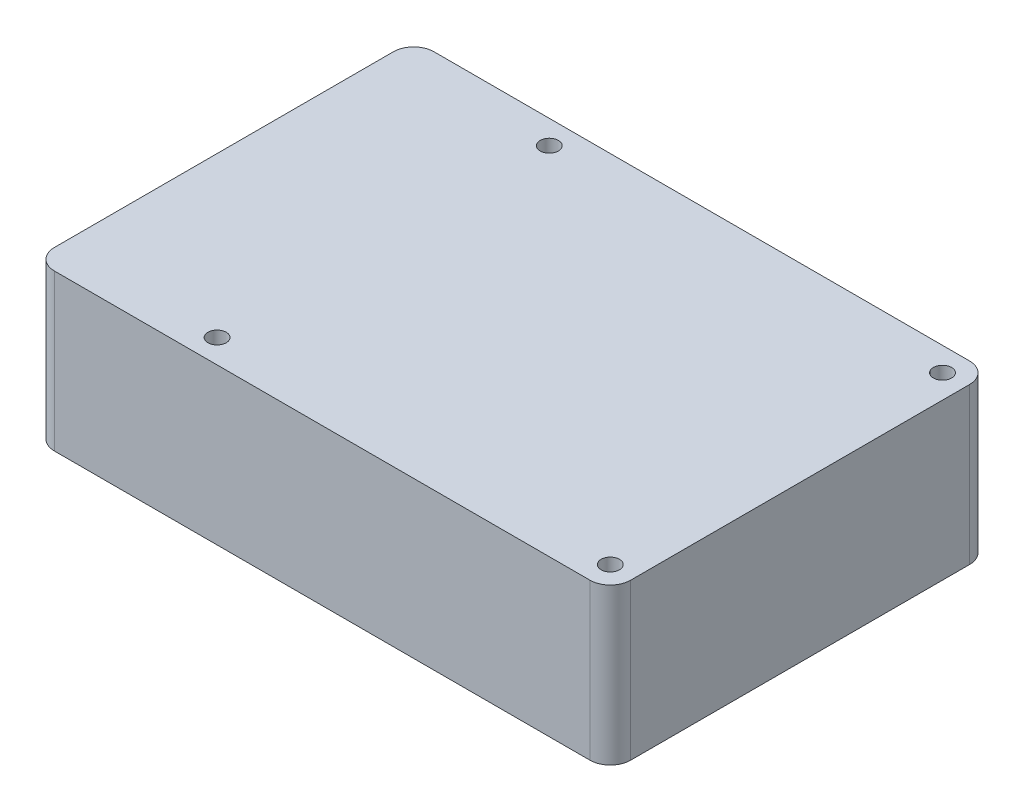
SolidWorks part; units mm, degrees
ref_plane "Alzado" through (0, 0, 0) normal (0, 0, 1) x (1, 0, 0)
ref_plane "Planta" through (0, 0, 0) normal (0, 1, 0) x (1, 0, 0)
ref_plane "Vista lateral" through (0, 0, 0) normal (1, 0, 0) x (0, 0, -1)
sketch "Croquis1" plane through (0, 0, 0) normal (0, 1, 0) x (1, 0, 0)
  line L1 (42.5, -28) -> (-42.5, -28)
  line L2 (42.5, -28) -> (42.5, 28)
  line L3 (42.5, 28) -> (-42.5, 28)
  line L4 (-42.5, -28) -> (-42.5, 28)
  line L5 (42.5, -28) -> (-42.5, 28) construction
  line L6 (42.5, 28) -> (-42.5, -28) construction
  point P0 (0, 0)
  dimension "D1" = 85
  dimension "D2" = 56
extrude "Saliente-Extruir1" add sketch "Croquis1" along normal blind 23
fillet "Redondeo1" radius 3 4 edges at (-42.5, 11.5, -28) (42.5, 11.5, -28) (-42.5, 11.5, 28) (42.5, 11.5, 28)
sketch "Croquis2" plane through (0, 23, 0) normal (0, 1, 0) x (1, 0, 0)
  line L0 (42.5, -25) -> (42.5, 25) construction
  line L5 (-19, 24.5) -> (39, 24.5) construction
  line L6 (-19, 24.5) -> (-19, -24.5) construction
  line L7 (-19, -24.5) -> (39, -24.5) construction
  line L8 (39, 24.5) -> (39, -24.5) construction
  circle A0 centre (-19, 24.5) radius 1.35
  circle A4 centre (39, 24.5) radius 1.35
  circle A5 centre (39, -24.5) radius 1.35
  circle A6 centre (-19, -24.5) radius 1.35
  point P8 (-19, 0)
  dimension "D4" = 2.7
  dimension "D1" = 3.5
  dimension "D2" = 49
  dimension "D3" = 58
extrude "Cortar-Extruir1" cut sketch "Croquis2" against normal through all
sketch "Croquis3" plane through (0, 0, 0) normal (0, -1, 0) x (1, 0, 0)
  line L0 (-39.5, 28) -> (39.5, 28) construction
  line L1 (39.5, -28) -> (-39.5, -28) construction
  line L13 (-44.25, -35.15) -> (44.25, -35.15)
  line L15 (44.25, 35.15) -> (-44.25, 35.15)
  line L18 (49.25, 25) -> (49.25, -25)
  line L19 (49.25, 30.15) -> (49.25, -30.15)
  line L21 (-49.25, -25) -> (-49.25, 25)
  line L22 (-49.25, -30.15) -> (-49.25, 30.15)
  arc A0 (49.25, 30.15) -> (44.25, 35.15) centre (44.25, 30.15) ccw
  arc A1 (44.25, -35.15) -> (49.25, -30.15) centre (44.25, -30.15) ccw
  arc A2 (-49.25, -30.15) -> (-44.25, -35.15) centre (-44.25, -30.15) ccw
  arc A3 (-49.25, 30.15) -> (-44.25, 35.15) centre (-44.25, 30.15) cw
  dimension "D5" = 5
  dimension "D1" = 7.15
  dimension "D2" = 7.15
  dimension "D3" = 6.75
  dimension "D4" = 6.75
extrude "Saliente-Extruir2" [suppressed] add sketch "Croquis3" against normal blind 33
sketch "Croquis4" plane through (0, 0, 0) normal (0, -1, 0) x (1, 0, 0)
  circle A1 centre (-19, 24.5) radius 1.35
  circle A2 centre (-19, 24.5) radius 1.35
  circle A3 centre (39, 24.5) radius 1.35
  circle A4 centre (39, 24.5) radius 1.35
  circle A5 centre (39, -24.5) radius 1.35
  circle A6 centre (39, -24.5) radius 1.35
  circle A7 centre (-19, -24.5) radius 1.35
  circle A8 centre (-19, -24.5) radius 1.35
  dimension "D1" = 0
  dimension "D2" = 0
  dimension "D3" = 0
  dimension "D4" = 0
extrude "Cortar-Extruir2" [suppressed] cut sketch "Croquis4" against normal through all
